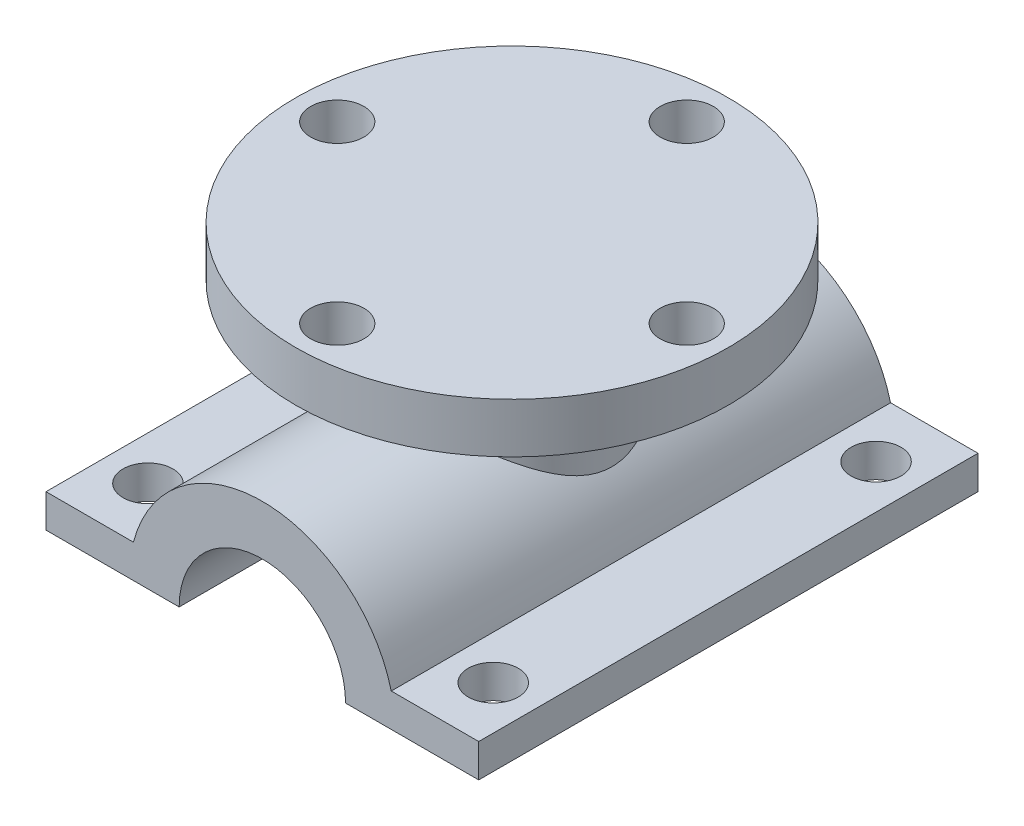
SolidWorks part; units mm, degrees
ref_plane "前视基准面" through (0, 0, 0) normal (0, 0, 1) x (1, 0, 0)
ref_plane "上视基准面" through (0, 0, 0) normal (0, 1, 0) x (1, 0, 0)
ref_plane "右视基准面" through (0, 0, 0) normal (1, 0, 0) x (0, 0, -1)
sketch "草图1" plane through (0, 0, 0) normal (0, 0, 1) x (1, 0, 0)
  line L0 (0, 0) -> (-8, 0) construction
  line L1 (-8, 0) -> (-13, 0)
  line L2 (-13, 0) -> (-13, 2)
  line L3 (-13, 2) -> (-7.746, 2)
  line L4 (-8, 0) -> (-5, 0)
  line L5 (0, 11.9859) -> (0, -9.7937) construction
  line L6 (0, 0) -> (8.9563, 0) construction
  line L7 (8, 0) -> (5, 0)
  line L8 (8, 0) -> (13, 0)
  line L9 (13, 0) -> (13, 2)
  line L10 (13, 2) -> (7.746, 2)
  arc A0 (5, 0) -> (-5, 0) centre (0, 0) ccw
  arc A1 (7.746, 2) -> (-7.746, 2) centre (0, 0) ccw
  dimension "D1" = 10
  dimension "D2" = 3
  dimension "D3" = 5
  dimension "D4" = 2
extrude "凸台-拉伸1" add sketch "草图1" along normal blind 30
sketch "草图2" plane through (0, 2, 0) normal (0, 1, 0) x (1, 0, 0)
  line L0 (10.373, 0) -> (10.373, -30) construction
  line L1 (13, 0) -> (7.746, 0) construction
  line L2 (13, -30) -> (7.746, -30) construction
  line L3 (10.373, -15) -> (0, -15) construction
  line L4 (0, -15) -> (0, -11.3332) construction
  circle A0 centre (10.373, -3.5) radius 1.5
  circle A1 centre (10.373, -26.5) radius 1.5
  circle A2 centre (-10.373, -26.5) radius 1.5
  circle A3 centre (-10.373, -3.5) radius 1.5
  dimension "D1" = 3
  dimension "D2" = 3.5
extrude "切除-拉伸1" cut sketch "草图2" against normal blind 30
ref_plane "基准面1" through (0, 12, 0) normal (0, 1, 0) x (1, 0, 0)
sketch "草图3" plane through (0, 12, 0) normal (0, 1, 0) x (1, 0, 0)
  circle A0 centre (0, -15) radius 6
  dimension "D1" = 12
extrude "凸台-拉伸2" add sketch "草图3" against normal up to surface (4 mm away)
sketch "草图4" plane through (0, 12, 0) normal (0, 1, 0) x (1, 0, 0)
  circle A0 centre (0, -15) radius 13
  dimension "D1" = 26
extrude "凸台-拉伸3" add sketch "草图4" along normal blind 3
sketch "草图6" plane through (0, 15, 0) normal (0, 1, 0) x (1, 0, 0)
  circle A1 centre (0, -15) radius 10.5 construction
  circle A2 centre (10.5, -15) radius 1.6
  circle A3 centre (0, -25.5) radius 1.6
  circle A4 centre (-10.5, -15) radius 1.6
  circle A5 centre (0, -4.5) radius 1.6
  point P14 (0, -15)
  dimension "D2" = 21
  dimension "D3" = 3.2
  dimension "D4" = 4
extrude "切除-拉伸2" cut sketch "草图6" against normal blind 3
